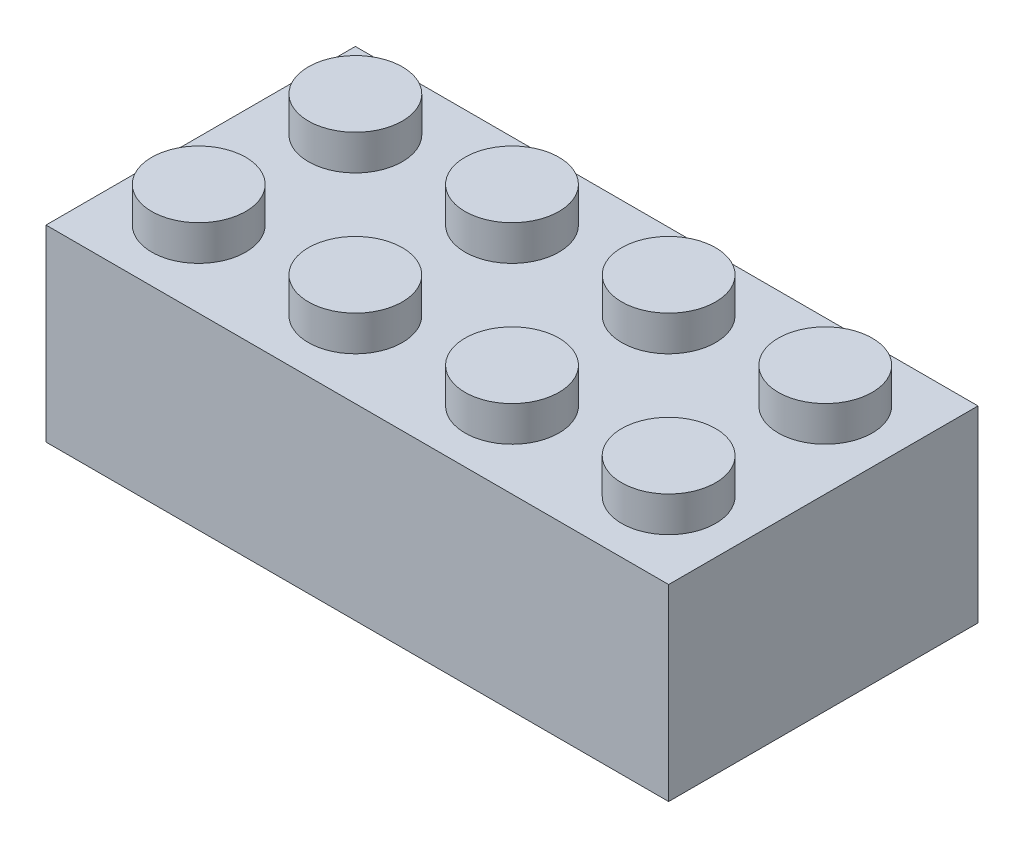
SolidWorks part; units mm, degrees
ref_plane "Front Plane" through (0, 0, 0) normal (0, 0, 1) x (1, 0, 0)
ref_plane "Top Plane" through (0, 0, 0) normal (0, 1, 0) x (1, 0, 0)
ref_plane "Right Plane" through (0, 0, 0) normal (1, 0, 0) x (0, 0, -1)
sketch "Sketch1" plane through (0, 0, 0) normal (0, 1, 0) x (1, 0, 0)
  line L1 (-15.9, 7.9) -> (15.9, 7.9)
  line L2 (-15.9, 7.9) -> (-15.9, -7.9)
  line L3 (-15.9, -7.9) -> (15.9, -7.9)
  line L4 (15.9, 7.9) -> (15.9, -7.9)
  dimension "D1" = 31.8
  dimension "D2" = 15.8
  dimension "D3" = 7.9
  dimension "D4" = 15.9
extrude "Boss-Extrude1" add sketch "Sketch1" along normal blind 9.6
sketch "Sketch2" plane through (0, 9.6, 0) normal (0, 1, 0) x (1, 0, 0)
  line L0 (0, 0) -> (21.1082, 0) construction
  circle A0 centre (-4, 4) radius 2.4
  circle A1 centre (-12, 4) radius 2.4
  circle A2 centre (4, 4) radius 2.4
  circle A3 centre (12, 4) radius 2.4
  circle A4 centre (12, -4) radius 2.4
  circle A5 centre (4, -4) radius 2.4
  circle A6 centre (-4, -4) radius 2.4
  circle A7 centre (-12, -4) radius 2.4
  dimension "D1" = 4.8
  dimension "D2" = 4
  dimension "D3" = 4
  dimension "D4" = 2
  dimension "D5" = 3
extrude "Boss-Extrude2" add sketch "Sketch2" along normal blind 1.8
sketch "Sketch4" plane through (0, 0, 0) normal (0, -1, 0) x (-1, 0, 0)
  line L0 (0, 0) -> (0, -9.1142) construction
  line L1 (8.5446, 0) -> (-10.8864, 0) construction
  line L2 (14.7, 3.3987) -> (14.7, -3.3987)
  line L3 (14.7, -3.3987) -> (14.5, -3.3987)
  line L4 (14.5, -3.3987) -> (14.5, -4.6013)
  line L5 (14.5, -4.6013) -> (14.7, -4.6013)
  line L6 (14.7, -4.6013) -> (14.7, -6.7)
  line L7 (14.7, -6.7) -> (12.6, -6.7)
  line L8 (12.6, -6.7) -> (12.6, -6.5)
  line L9 (12.6, -6.5) -> (11.4, -6.5)
  line L10 (11.4, -6.5) -> (11.4, -6.7)
  line L11 (11.4, -6.7) -> (4.6013, -6.7)
  line L12 (4.6013, -6.7) -> (4.6013, -6.5)
  line L13 (4.6013, -6.5) -> (3.3987, -6.5)
  line L14 (3.3987, -6.5) -> (3.3987, -6.7)
  line L15 (3.3987, -6.7) -> (-3.3987, -6.7)
  line L16 (15.9, 7.9) -> (15.9, -7.9) construction
  line L17 (15.9, -7.9) -> (-15.9, -7.9) construction
  line L18 (3.3987, 6.7) -> (-3.3987, 6.7)
  line L19 (3.3987, 6.5) -> (3.3987, 6.7)
  line L20 (4.6013, 6.5) -> (3.3987, 6.5)
  line L21 (4.6013, 6.7) -> (4.6013, 6.5)
  line L22 (11.4, 6.7) -> (4.6013, 6.7)
  line L23 (11.4, 6.5) -> (11.4, 6.7)
  line L24 (12.6, 6.5) -> (11.4, 6.5)
  line L25 (12.6, 6.7) -> (12.6, 6.5)
  line L26 (14.7, 6.7) -> (12.6, 6.7)
  line L27 (14.7, 4.6013) -> (14.7, 6.7)
  line L28 (14.5, 4.6013) -> (14.7, 4.6013)
  line L29 (14.5, 3.3987) -> (14.5, 4.6013)
  line L30 (14.7, 3.3987) -> (14.5, 3.3987)
  line L31 (-14.7, 3.3987) -> (-14.5, 3.3987)
  line L32 (-14.5, 3.3987) -> (-14.5, 4.6013)
  line L33 (-14.5, 4.6013) -> (-14.7, 4.6013)
  line L34 (-14.7, 4.6013) -> (-14.7, 6.7)
  line L35 (-14.7, 6.7) -> (-12.6, 6.7)
  line L36 (-12.6, 6.7) -> (-12.6, 6.5)
  line L37 (-12.6, 6.5) -> (-11.4, 6.5)
  line L38 (-11.4, 6.5) -> (-11.4, 6.7)
  line L39 (-11.4, 6.7) -> (-4.6013, 6.7)
  line L40 (-4.6013, 6.7) -> (-4.6013, 6.5)
  line L41 (-4.6013, 6.5) -> (-3.3987, 6.5)
  line L42 (-3.3987, 6.5) -> (-3.3987, 6.7)
  line L43 (-3.3987, -6.5) -> (-3.3987, -6.7)
  line L44 (-4.6013, -6.5) -> (-3.3987, -6.5)
  line L45 (-4.6013, -6.7) -> (-4.6013, -6.5)
  line L46 (-11.4, -6.7) -> (-4.6013, -6.7)
  line L47 (-11.4, -6.5) -> (-11.4, -6.7)
  line L48 (-12.6, -6.5) -> (-11.4, -6.5)
  line L49 (-12.6, -6.7) -> (-12.6, -6.5)
  line L50 (-14.7, -6.7) -> (-12.6, -6.7)
  line L51 (-14.7, -4.6013) -> (-14.7, -6.7)
  line L52 (-14.5, -4.6013) -> (-14.7, -4.6013)
  line L53 (-14.5, -3.3987) -> (-14.5, -4.6013)
  line L54 (-14.7, -3.3987) -> (-14.5, -3.3987)
  line L55 (-14.7, 3.3987) -> (-14.7, -3.3987)
  point P23 (0, 0)
  point P24 (14.5, -4.0802)
  point P25 (14.5, -4)
  point P28 (0, 0)
  point P29 (0, 0)
  point P30 (12, -6.5)
  point P31 (4, -6.5)
  point P33 (14.7, 0)
  point P47 (0, -6.7)
  point P48 (0, 6.7)
  point P72 (-14.7, 0)
  dimension "D1" = 1.2
  dimension "D2" = 0.2
  dimension "D3" = 1.2026
  dimension "D4" = 4
  dimension "D5" = 1.2
  dimension "D6" = 1.2
  dimension "D7" = 1.2026
  dimension "D8" = 0.2
  dimension "D9" = 0.2
  dimension "D10" = 12
  dimension "D11" = 4
extrude "Cut-Extrude8" cut sketch "Sketch4" against normal blind 8.6
sketch "Sketch5" plane through (0, 8.6, 0) normal (0, -1, 0) x (-1, 0, 0)
  circle A0 centre (12, -4) radius 1.3
  circle A1 centre (4, -4) radius 1.3
  circle A2 centre (-4, -4) radius 1.3
  circle A3 centre (-12, -4) radius 1.3
  circle A4 centre (4, 4) radius 1.3
  circle A5 centre (-4, 4) radius 1.3
  circle A6 centre (-12, 4) radius 1.3
  circle A7 centre (12, 4) radius 1.3
  dimension "D1" = 2.6
  dimension "D2" = 12
  dimension "D3" = 4
  dimension "D4" = 4
  dimension "D5" = 2
extrude "Cut-Extrude9" cut sketch "Sketch5" against normal blind 1.7
sketch "Sketch6" plane through (0, 8.6, 0) normal (0, -1, 0) x (-1, 0, 0)
  circle A0 centre (0, 0) radius 3.25
  circle A1 centre (0, 0) radius 2.05
  circle A2 centre (8, 0) radius 2.05
  circle A3 centre (8, 0) radius 3.25
  circle A4 centre (-8, 0) radius 2.05
  circle A5 centre (-8, 0) radius 3.25
  dimension "D1" = 6.5
  dimension "D2" = 1.2
  dimension "D3" = 2
  dimension "D4" = 2
extrude "Boss-Extrude3" add sketch "Sketch6" along normal blind 8.6
sketch "Sketch7" plane through (0, 8.6, 0) normal (0, -1, 0) x (-1, 0, 0)
  line L0 (0.55, -3.2031) -> (0.55, -6.7)
  line L1 (-3.3987, -6.7) -> (3.3987, -6.7) construction
  line L2 (0.55, -6.7) -> (-0.55, -6.7)
  line L3 (-0.55, -6.7) -> (-0.55, -3.2031)
  line L4 (0, 0) -> (0, -10.0319) construction
  line L5 (20.2221, 0) -> (13.5131, 0) construction
  line L6 (-0.55, 6.7) -> (-0.55, 3.2031)
  line L7 (0.55, 6.7) -> (-0.55, 6.7)
  line L8 (0.55, 3.2031) -> (0.55, 6.7)
  circle A0 centre (0, 0) radius 3.25 construction
  circle A1 centre (0, 0) radius 3.25 construction
  arc A2 (0.55, -3.2031) -> (-0.55, -3.2031) centre (0, 0) cw
  arc A3 (0.55, 3.2031) -> (-0.55, 3.2031) centre (0, 0) ccw
  dimension "D2" = 3.25
  dimension "D3" = 3.25
  dimension "D1" = 1.1
extrude "Boss-Extrude4" add sketch "Sketch7" along normal blind 6.3
